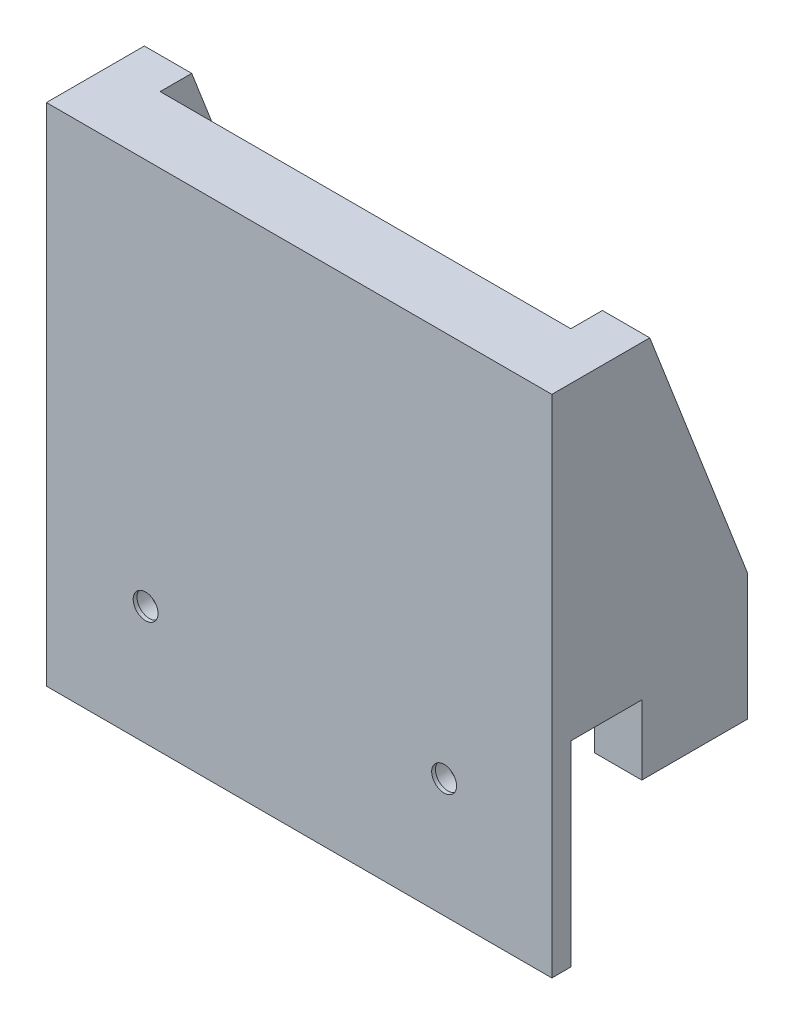
SolidWorks part; units mm, degrees
material "Plain Carbon Steel"
ref_plane "Front Plane" through (0, 0, 0) normal (0, 0, 1) x (1, 0, 0)
ref_plane "Top Plane" through (0, 0, 0) normal (0, 1, 0) x (1, 0, 0)
ref_plane "Right Plane" through (0, 0, 0) normal (1, 0, 0) x (0, 0, -1)
sketch "Sketch1" plane through (0, 0, 0) normal (0, 0, 1) x (1, 0, 0)
  line L1 (-101.6, 0) -> (0, 0)
  line L2 (-101.6, 0) -> (-101.6, 101.6)
  line L3 (-101.6, 101.6) -> (0, 101.6)
  line L4 (0, 0) -> (0, 101.6)
  dimension "D1" = 101.6
extrude "Boss-Extrude1" add sketch "Sketch1" along normal blind 3.81
hole_wizard "M6x1.0 Tapped Hole1" positions "Sketch2" profile "Sketch3" tap size "M6x1.0" standard "ANSI Metric" end condition through all
sketch "Sketch2" plane through (-50.8, -38.1, 0) normal (0, 0, -1) x (-1, 0, 0)
  line L0 (-29.143, 61.9649) -> (30.8599, 61.9649) construction
  line L1 (0, 76.452) -> (0, 39.5098) construction
  point P0 (-29.143, 61.9649)
  point P1 (30.8599, 61.9649)
sketch "Sketch3" plane through (-21.657, 23.8649, 0) normal (1, 0, 0) x (0, 1, 0)
  line L0 (0, 0) -> (0, 3.81)
  line L1 (0, 3.81) -> (2.5, 3.81)
  line L3 (2.5, 3.81) -> (2.5, 3.048)
  line L4 (2.5, 3.048) -> (3, 3.048)
  line L5 (3, 3.048) -> (3, 0)
  line L7 (3, 0) -> (0, 0)
  line L11 (0, -6.35) -> (0, 107.95) construction
  dimension "Thru Tap Drill Dia." = 5
  dimension "Thru Tap Drill Depth" = 3.81
  dimension "Thread Major Dia." = 6
  dimension "Thread Depth" = 3.048
sketch "Sketch4" plane through (0, 0, 0) normal (0, 0, -1) x (-1, 0, 0)
  line L0 (101.6, 101.6) -> (101.6, 0) construction
  line L1 (0, 101.6) -> (101.6, 101.6)
  line L2 (0, 101.6) -> (0, 39.37)
  line L3 (0, 39.37) -> (101.6, 39.37)
  line L4 (101.6, 101.6) -> (101.6, 39.37)
  line L5 (101.6, 39.37) -> (0, 39.37) construction
  line L6 (0, 0) -> (0, 101.6) construction
extrude "Boss-Extrude2" add sketch "Sketch4" along normal blind 9.525
sketch "Sketch5" plane through (0, 0, 0) normal (1, 0, 0) x (0, 0, -1)
  line L0 (9.525, 101.6) -> (15.875, 101.6)
  line L1 (15.875, 101.6) -> (35.5342, 50.8)
  line L2 (35.5342, 50.8) -> (35.5342, 25.4)
  line L3 (35.5342, 25.4) -> (14.2748, 25.4)
  line L4 (14.2748, 25.4) -> (14.2748, 39.37)
  line L5 (14.2748, 39.37) -> (9.525, 39.37)
  line L6 (9.525, 39.37) -> (9.525, 101.6)
  dimension "D1" = 6.35
  dimension "D2" = 25.4
extrude "Boss-Extrude3" add sketch "Sketch5" against normal blind 9.525
sketch "Sketch6" plane through (-101.6, 0, 0) normal (-1, 0, 0) x (0, 0, 1)
  line L7 (-9.525, 39.37) -> (-9.525, 101.6)
  line L8 (-9.525, 101.6) -> (-15.875, 101.6)
  line L9 (-15.875, 101.6) -> (-35.5342, 50.8)
  line L10 (-35.5342, 50.8) -> (-35.5342, 25.4)
  line L11 (-35.5342, 25.4) -> (-14.2748, 25.4)
  line L12 (-14.2748, 25.4) -> (-14.2748, 39.37)
  line L13 (-14.2748, 39.37) -> (-9.525, 39.37)
  line L14 (-9.525, 39.37) -> (-9.525, 101.6)
  line L15 (-9.525, 101.6) -> (-15.875, 101.6)
  line L16 (-15.875, 101.6) -> (-35.5342, 50.8)
  line L17 (-35.5342, 50.8) -> (-35.5342, 25.4)
  line L18 (-35.5342, 25.4) -> (-14.2748, 25.4)
  line L19 (-14.2748, 25.4) -> (-14.2748, 39.37)
  line L20 (-14.2748, 39.37) -> (-9.525, 39.37)
  dimension "D1" = 0
extrude "Boss-Extrude4" add sketch "Sketch6" against normal blind 9.525
equation "\"delta-z\" = 1.5"
equation "\"total-height\" = 3.28"
equation "\"mid-height\" = 1.5"
equation "\"jaw-width\" = 4"
equation "\"jaw-height\" = \"total-height\" - \"mid-height\""
equation "\"max-tube-diam\" = 3.5"
equation "\"v-block-notch-height\" = 1.5"
equation "\"v-block-notch-angle\" = 120"
equation "\"jaw-mod-plate-thickness\" = .375"
equation "\"jaw-mod-height\" =  \"max-tube-diam\"/2 + \"delta-z\" + \"v-block-notch-height\"/2"
equation "\"jaw-travel\" = 4.45"
equation "\"rib-top-width\" = 0.5"
equation "\"rib-side-width\" = 0.5"
equation "\"quarter-twenty-close-clearance\" = .257"
equation "\"box-way-width\" = 1.5"
equation "\"box-way-depth\" = 1.5"
equation "\"screw-OD\" = .625"
equation "\"screw-reduced-diam\" = .47"
equation "\"pressure-plate-OD\" = 6.75"
equation "\"swivel-cleat-thick\" = .5"
equation "\"swivel-gap\" = .02"
equation "\"D1@Sketch1\"=\"jaw-mod-height\""
equation "\"jaw-mod-plate-extension-thickness\" = .15"
equation "\"D1@Boss-Extrude1\"=\"jaw-mod-plate-extension-thickness\""
equation "\"D1@Boss-Extrude2\"=\"jaw-mod-plate-thickness\""
equation "\"D1@Boss-Extrude3\"=\"jaw-mod-plate-thickness\""
equation "\"D1@Boss-Extrude4\"=\"jaw-mod-plate-thickness\""
